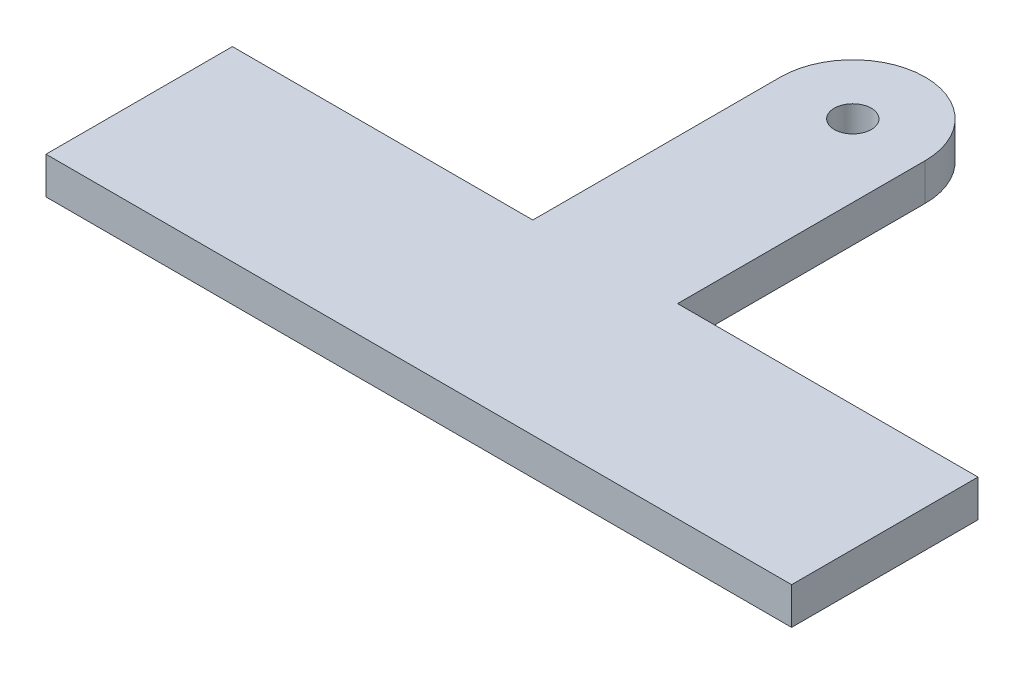
SolidWorks part; units mm, degrees
ref_plane "Front Plane" through (0, 0, 0) normal (0, 0, 1) x (1, 0, 0)
ref_plane "Top Plane" through (0, 0, 0) normal (0, 1, 0) x (1, 0, 0)
ref_plane "Right Plane" through (0, 0, 0) normal (1, 0, 0) x (0, 0, -1)
sketch "Sketch1" plane through (0, 0, 0) normal (0, 1, 0) x (1, 0, 0)
  line L0 (4.9638, 0) -> (25.5651, 0)
  line L1 (-25.5651, 0) -> (-4.9638, 0)
  line L2 (-25.5651, 0) -> (-25.5651, -12.7825)
  line L3 (-25.5651, -12.7825) -> (25.5651, -12.7825)
  line L4 (25.5651, 0) -> (25.5651, -12.7825)
  line L5 (-4.9638, 0) -> (4.9638, 0) construction
  line L6 (-4.9638, 0) -> (-4.9638, 16.9801)
  line L8 (4.9638, 0) -> (4.9638, 16.9801)
  circle A0 centre (0, 16.9801) radius 1.27
  arc A1 (-4.9638, 16.9801) -> (4.9638, 16.9801) centre (0, 16.9801) cw
  dimension "D1" = 2.54
extrude "Boss-Extrude1" add sketch "Sketch1" along normal mid plane 2.54
